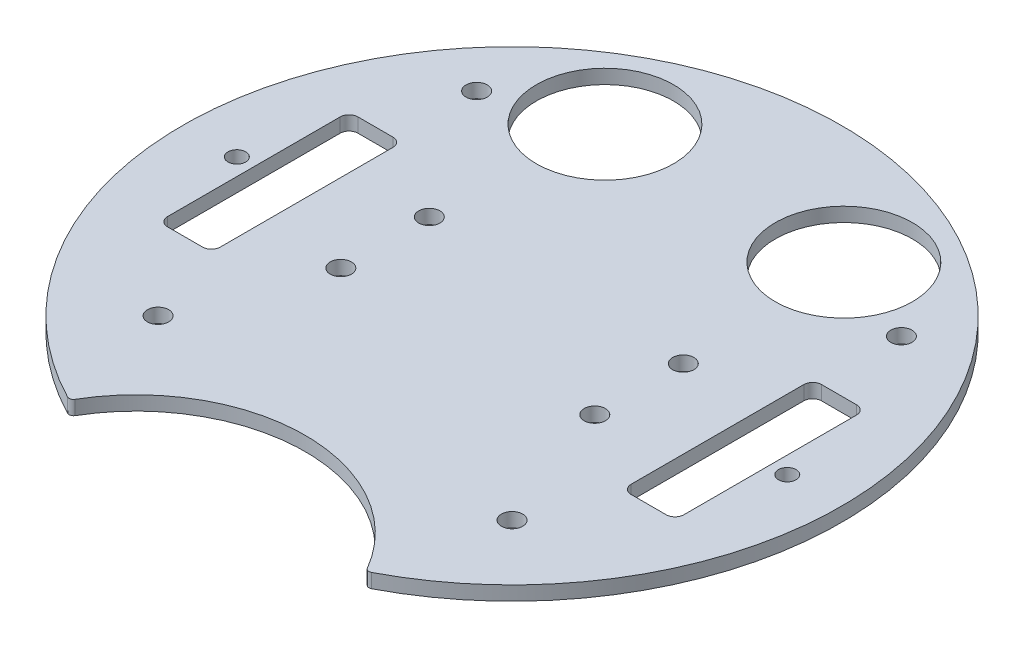
SolidWorks part; units mm, degrees
material "Plain Carbon Steel"
ref_plane "Front Plane" through (0, 0, 0) normal (0, 0, 1) x (1, 0, 0)
ref_plane "Top Plane" through (0, 0, 0) normal (0, 1, 0) x (1, 0, 0)
ref_plane "Right Plane" through (0, 0, 0) normal (1, 0, 0) x (0, 0, -1)
sketch "Sketch1" plane through (0, 0, 0) normal (0, 1, 0) x (1, 0, 0)
  line L1 (0, -85) -> (0, 0) construction
  arc A0 (34.3603, -66.1031) -> (-34.3603, -66.1031) centre (0, 0) ccw
  arc A1 (33.0354, -65.7199) -> (-33.0354, -65.7199) centre (0, -85) ccw
  arc A2 (34.3603, -66.1031) -> (33.0354, -65.7199) centre (33.8991, -65.2158) cw
  arc A3 (-33.0354, -65.7199) -> (-34.3603, -66.1031) centre (-33.8991, -65.2158) cw
  dimension "D1" = 149
  dimension "D2" = 76.5
  dimension "D4" = 1
  dimension "D3" = 85
extrude "Boss-Extrude1" add sketch "Sketch1" along normal blind 3.2
sketch "solenoid placement" plane through (0, 3.2, 0) normal (0, 1, 0) x (1, 0, 0)
  line L0 (0, 0) -> (0, -36) construction
  line L1 (0, -36) -> (0, -46.75) construction
  line L2 (-19, -36) -> (19, -36)
  line L3 (-19, -36) -> (-19, 28)
  line L4 (-19, 28) -> (19, 28)
  line L5 (19, -36) -> (19, 28)
  circle A1 centre (0, 0) radius 74.5 construction
  arc A2 (34.3603, -66.1031) -> (-34.3603, -66.1031) centre (0, 0) ccw construction
  arc A3 (33.0354, -65.7199) -> (-33.0354, -65.7199) centre (0, -85) ccw construction
  dimension "D1" = 64
  dimension "D2" = 36
  dimension "D4" = 38
sketch "Sketch2" plane through (0, 3.2, 0) normal (0, 1, 0) x (1, 0, 0)
  line L1 (-57.47, 20.6344) -> (-47.31, 20.6344) construction
  line L2 (-57.47, 20.6344) -> (-57.47, -20.6344) construction
  line L3 (-57.47, -20.6344) -> (-47.31, -20.6344) construction
  line L4 (-47.31, 20.6344) -> (-47.31, -20.6344) construction
  line L8 (-57.77, -20.9344) -> (-47.01, -20.9344)
  line L9 (-47.01, 20.9344) -> (-47.01, -20.9344)
  line L10 (-57.77, 20.9344) -> (-47.01, 20.9344)
  line L11 (-57.77, 20.9344) -> (-57.77, -20.9344)
  line L12 (0, 0) -> (0, 74.5) construction
  line L13 (47.31, 20.6344) -> (47.31, -20.6344) construction
  line L14 (57.47, -20.6344) -> (47.31, -20.6344) construction
  line L15 (57.47, 20.6344) -> (57.47, -20.6344) construction
  line L16 (57.47, 20.6344) -> (47.31, 20.6344) construction
  line L17 (57.77, 20.9344) -> (57.77, -20.9344)
  line L18 (57.77, 20.9344) -> (47.01, 20.9344)
  line L19 (47.01, 20.9344) -> (47.01, -20.9344)
  line L20 (57.77, -20.9344) -> (47.01, -20.9344)
  arc A0 (34.3603, -66.1031) -> (-34.3603, -66.1031) centre (0, 0) ccw construction
  dimension "D1" = 0.3
extrude "Cut-Extrude1" cut sketch "Sketch2" against normal through all
sketch "Sketch3" plane through (0, 0, 0) normal (0, -1, 0) x (1, 0, 0)
  line L0 (0, 0) -> (0, -74.5) construction
  circle A0 centre (-62.2, 0) radius 2
  circle A1 centre (-28.7007, 10) radius 2.4
  circle A2 centre (-28.7007, -10) radius 2.4
  arc A3 (-34.3603, 66.1031) -> (34.3603, 66.1031) centre (0, 0) ccw construction
  circle A4 centre (28.7007, -10) radius 2.4
  circle A5 centre (28.7007, 10) radius 2.4
  circle A6 centre (62.2, 0) radius 2
  dimension "D1" = 4
  dimension "D2" = 4.8
extrude "Cut-Extrude2" cut sketch "Sketch3" against normal through all
sketch "Sketch4" plane through (0, 3.2, 0) normal (0, 1, 0) x (1, 0, 0)
  line L0 (0, 0) -> (0, 74.5) construction
  line L1 (0, 48) -> (-27, 48) construction
  circle A0 centre (-27, 48) radius 15
  arc A1 (34.3603, -66.1031) -> (-34.3603, -66.1031) centre (0, 0) ccw construction
  circle A2 centre (27, 48) radius 15
  dimension "D1" = 30
  dimension "D2" = 48
  dimension "D3" = 27
extrude "Cut-Extrude3" cut sketch "Sketch4" against normal through all
sketch "Sketch5" plane through (0, 3.2, 0) normal (0, 1, 0) x (1, 0, 0)
  line L0 (0, 0) -> (0, 74.5) construction
  line L1 (-56.3558, 21.5201) -> (-48.4242, 21.5201)
  line L2 (-58.3558, 19.5201) -> (-58.3558, -19.5201)
  line L3 (-56.3558, -21.5201) -> (-48.4242, -21.5201)
  line L4 (-46.4242, 19.5201) -> (-46.4242, -19.5201)
  line L5 (46.4242, 19.5201) -> (46.4242, -19.5201)
  line L6 (56.3558, -21.5201) -> (48.4242, -21.5201)
  line L7 (58.3558, 19.5201) -> (58.3558, -19.5201)
  line L8 (56.3558, 21.5201) -> (48.4242, 21.5201)
  arc A0 (-58.3558, -19.5201) -> (-56.3558, -21.5201) centre (-56.3558, -19.5201) ccw
  arc A1 (-48.4242, -21.5201) -> (-46.4242, -19.5201) centre (-48.4242, -19.5201) ccw
  arc A2 (-48.4242, 21.5201) -> (-46.4242, 19.5201) centre (-48.4242, 19.5201) cw
  arc A3 (-56.3558, 21.5201) -> (-58.3558, 19.5201) centre (-56.3558, 19.5201) ccw
  arc A4 (34.3603, -66.1031) -> (-34.3603, -66.1031) centre (0, 0) ccw construction
  arc A5 (56.3558, 21.5201) -> (58.3558, 19.5201) centre (56.3558, 19.5201) cw
  arc A6 (48.4242, 21.5201) -> (46.4242, 19.5201) centre (48.4242, 19.5201) ccw
  arc A7 (48.4242, -21.5201) -> (46.4242, -19.5201) centre (48.4242, -19.5201) cw
  arc A8 (58.3558, -19.5201) -> (56.3558, -21.5201) centre (56.3558, -19.5201) cw
  point P15 (-57.77, 20.9344)
  dimension "D1" = 2
extrude "Cut-Extrude4" cut sketch "Sketch5" against normal through all
sketch "Sketch6" plane through (0, 3.2, 0) normal (0, 1, 0) x (1, 0, 0)
  line L0 (0, 74.5) -> (0, -46.75) construction
  circle A0 centre (48, 40) radius 2.4
  circle A1 centre (-40, -40) radius 2.4
  arc A4 (34.3603, -66.1031) -> (-34.3603, -66.1031) centre (0, 0) ccw construction
  arc A5 (33.0354, -65.7199) -> (-33.0354, -65.7199) centre (0, -85) ccw construction
  circle A6 centre (40, -40) radius 2.4
  circle A7 centre (-48, 40) radius 2.4
  dimension "D3" = 4.8
  dimension "D1" = 40
  dimension "D2" = 40
  dimension "D4" = 48
  dimension "D5" = 40
extrude "Cut-Extrude5" cut sketch "Sketch6" against normal through all
chamfer "Chamfer1" [suppressed] distance 2 angle 41
sketch "Sketch8" plane through (0, 3.2, 0) normal (0, 1, 0) x (1, 0, 0)
  circle A0 centre (-27, 48) radius 15.5
  circle A1 centre (27, 48) radius 15.5
  dimension "D1" = 31
extrude "Cut-Extrude6" cut sketch "Sketch8" against normal through all
equation "\"smallPulleyTeeth\"= 30"
equation "\"largePulleyTeeth\"= 30"
equation "\"eighthThick\"= 3.0mm"
equation "\"sixteenthThick\"= 1.7mm"
equation "\"quarterThick\"=6.0mm"
equation "\"OD\"= 145mm"
equation "\"puckAngle\"= 60.5deg"
equation "\"puckDiam\"= 76.5mm"
equation "\"D2@Sketch1\"=\"puckDiam\""
equation "\"D1@Boss-Extrude1\"=\"eighthThick\""
equation "\"axlePress\"= 5.9mm"
equation "\"press\"= 0.2mm"
equation "\"wheelClear\"= 0.3mm"
equation "\"D1@Sketch2\"=\"wheelClear\""
equation "\"10-32clear\"= 4.8mm"
equation "\"6-32clear\"= 3.3mm"
equation "\"8-32clear\"= 4.0mm"
equation "\"wheelHeight\"= 22mm"
equation "\"D1@Sketch3\"=\"8-32clear\""
equation "\"D2@Sketch3\"=\"10-32clear\""
equation "\"D3@Sketch6\"=\"10-32clear\""
equation "\"puckDist\"= 85mm"
equation "\"4-40clear\"= 3.0mm"
equation "\"wheelWell\"= 65mm"
equation "\"D3@Sketch1\"=\"puckDist\""
